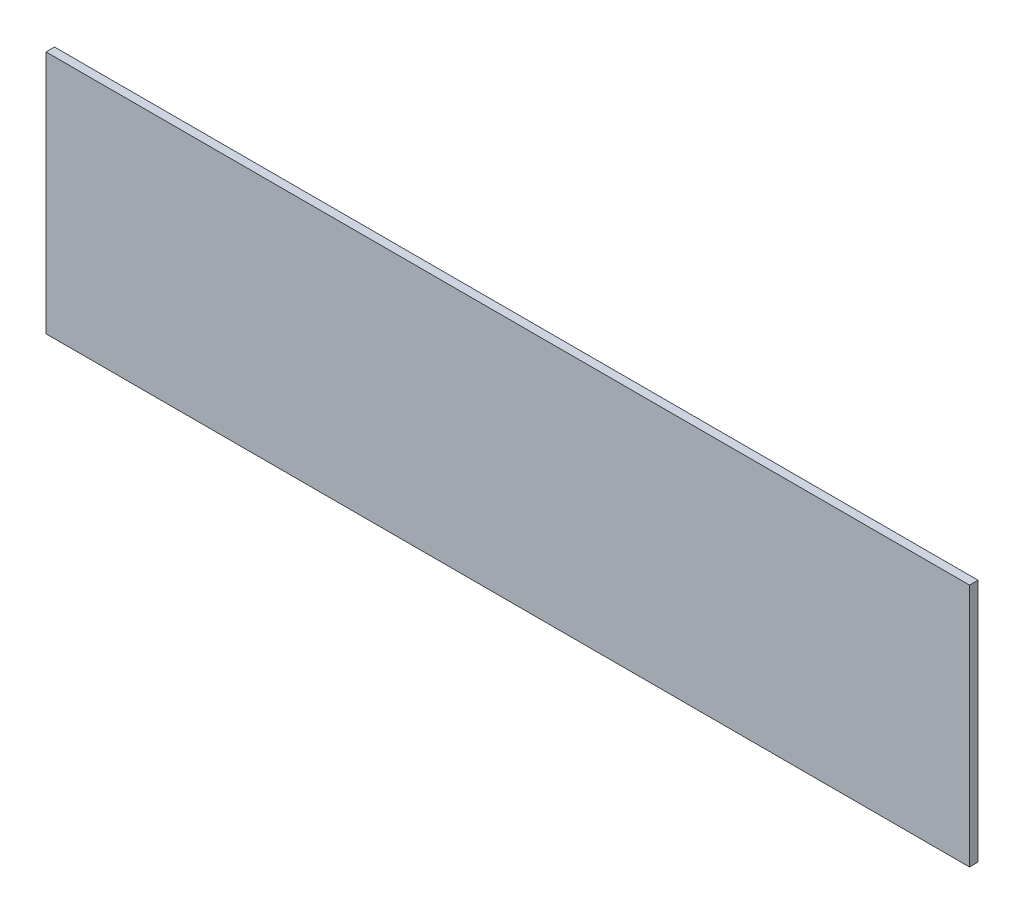
SolidWorks part; units mm, degrees
ref_plane "Ön Düzlem" through (0, 0, 0) normal (0, 0, 1) x (1, 0, 0)
ref_plane "Üst Düzlem" through (0, 0, 0) normal (0, 1, 0) x (1, 0, 0)
ref_plane "Sağ Düzlem" through (0, 0, 0) normal (1, 0, 0) x (0, 0, -1)
sketch "Sketch1" plane through (0, 0, 0) normal (0, 0, 1) x (1, 0, 0)
  line L1 (-217.5, 57.5) -> (217.5, 57.5)
  line L2 (-217.5, 57.5) -> (-217.5, -57.5)
  line L3 (-217.5, -57.5) -> (217.5, -57.5)
  line L4 (217.5, 57.5) -> (217.5, -57.5)
  line L5 (-217.5, 57.5) -> (217.5, -57.5) construction
  line L6 (-217.5, -57.5) -> (217.5, 57.5) construction
  point P0 (0, 0)
  dimension "D1" = 435
  dimension "D2" = 115
extrude "Boss-Extrude1" add sketch "Sketch1" along normal blind 4
